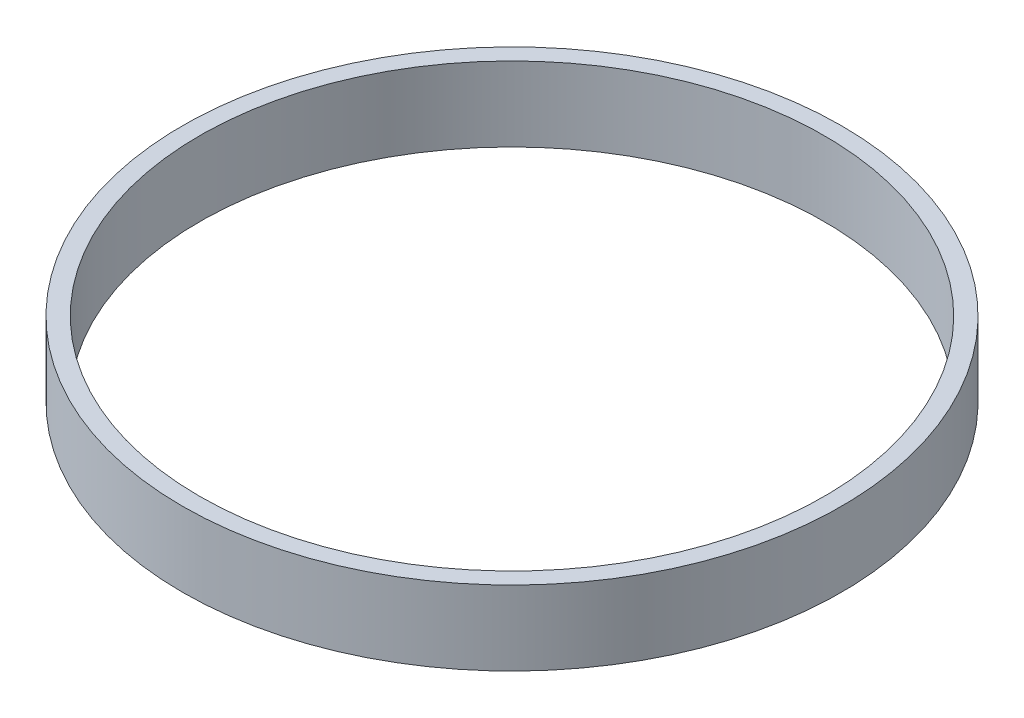
SolidWorks part; units mm, degrees
ref_plane "Front Plane" through (0, 0, 0) normal (0, 0, 1) x (1, 0, 0)
ref_plane "Top Plane" through (0, 0, 0) normal (0, 1, 0) x (1, 0, 0)
ref_plane "Right Plane" through (0, 0, 0) normal (1, 0, 0) x (0, 0, -1)
sketch "Sketch1" plane through (0, 0, 0) normal (0, 1, 0) x (1, 0, 0)
  circle A0 centre (0, 0) radius 57.5
  dimension "D1" = 115
extrude "Boss-Extrude1" add sketch "Sketch1" along normal blind 13
sketch "Sketch2" plane through (0, 13, 0) normal (0, 1, 0) x (1, 0, 0)
  circle A0 centre (0, 0) radius 54.5
extrude "Cut-Extrude1" cut sketch "Sketch2" against normal blind 13
